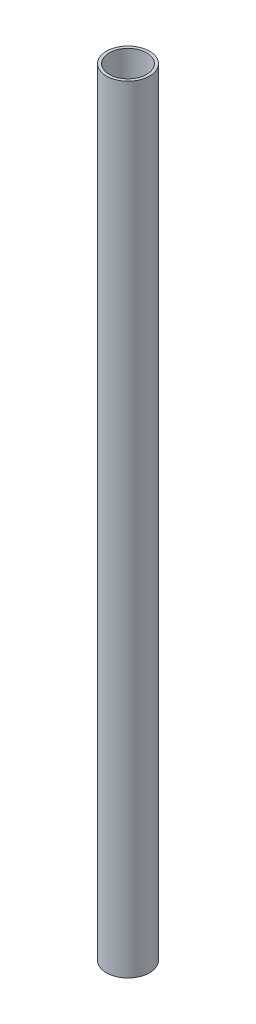
SolidWorks part; units mm, degrees
ref_plane "Front Plane" through (0, 0, 0) normal (0, 0, 1) x (1, 0, 0)
ref_plane "Top Plane" through (0, 0, 0) normal (0, 1, 0) x (1, 0, 0)
ref_plane "Right Plane" through (0, 0, 0) normal (1, 0, 0) x (0, 0, -1)
sketch "Sketch1" plane through (0, 0, 0) normal (0, 1, 0) x (1, 0, 0)
  circle A0 centre (0, 0) radius 7.5
  circle A1 centre (0, 0) radius 6.5
  dimension "D1" = 15
  dimension "D2" = 1
extrude "Boss-Extrude1" add sketch "Sketch1" along normal blind 270
